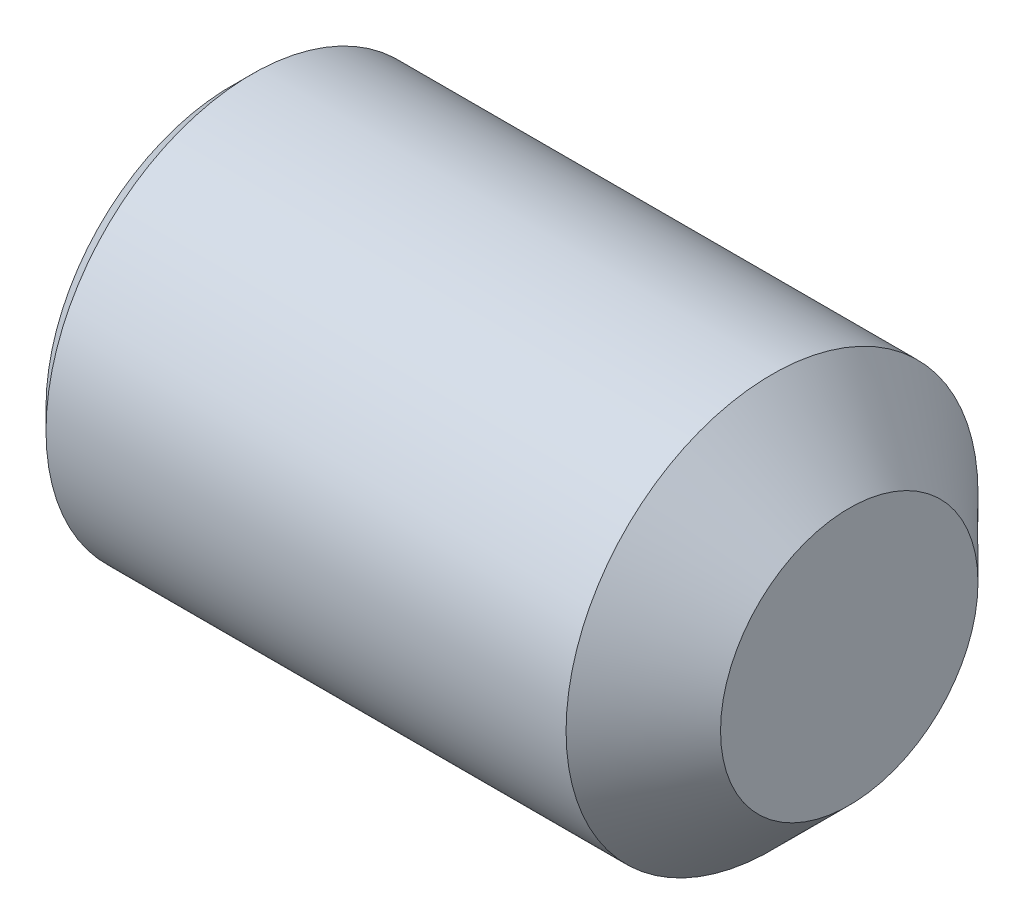
SolidWorks part; units mm, degrees
material "Galvanized Steel"
ref_plane "Front Plane" through (0, 0, 0) normal (0, 0, 1) x (1, 0, 0)
ref_plane "Top Plane" through (0, 0, 0) normal (0, 1, 0) x (1, 0, 0)
ref_plane "Right Plane" through (0, 0, 0) normal (1, 0, 0) x (0, 0, -1)
ref_plane "Plane4" through (0, 0, 0) normal (0, 0, -1) x (-1, 0, 0)
sketch "Sketch1" plane through (0, 0, 0) normal (0, 0, -1) x (-1, 0, 0)
  line L0 (-6, 2) -> (-6, 0)
  line L1 (-6, 0) -> (0, 0)
  line L2 (0, 0) -> (0, 2)
  line L3 (0, 2) -> (-6, 2)
  line L4 (-6, 0) -> (0, 0) construction
  line L5 (0, 0) -> (3.2611, 0) construction
  dimension "D1" = 6
  dimension "D2" = 4
revolve "Revolve1" add sketch "Sketch1" angle 360 about L4
cosmetic thread "Cosmetic Thread1" parameters "D2"=3.22
sketch "Sketch2" plane through (0, 0, 0) normal (-1, 0, 0) x (0, 0, 1)
  line L0 (0.5774, -1) -> (1.1547, 0)
  line L1 (1.1547, 0) -> (0.5774, 1)
  line L2 (0.5774, 1) -> (-0.5774, 1)
  line L3 (-0.5774, 1) -> (-1.1547, 0)
  line L4 (-1.1547, 0) -> (-0.5774, -1)
  line L5 (-0.5774, -1) -> (0.5774, -1)
  circle A0 centre (0, 0) radius 1 construction
  dimension "D1" = 2
extrude "Cut-Extrude1" cut sketch "Sketch2" against normal blind 2.3
chamfer "Chamfer1" distance 0.75 angle 45 1 edges at (6, 0, 2)
chamfer "Chamfer2" distance 0.2 angle 45 1 edges at (0, 0, 2)
sketch "Sketch3" [suppressed] plane through (0, 0, 0) normal (0, 1, 0) x (1, 0, 0)
  line L0 (0, 1.1547) -> (1.1547, 0)
  line L1 (1.1547, 0) -> (0, 0)
  line L2 (0, 1.8) -> (0, -1.8) construction
  line L3 (0, 0) -> (0, 1.1547)
  line L4 (2.3, 1.1547) -> (0, 1.1547) construction
  line L5 (1.1547, 0) -> (2.3, 0) construction
  line L6 (2.3, -0.5774) -> (2.3, 0.5774) construction
  dimension "D1" = 45
revolve "Cut-Revolve1" [suppressed] cut sketch "Sketch3" angle 360 about L5
